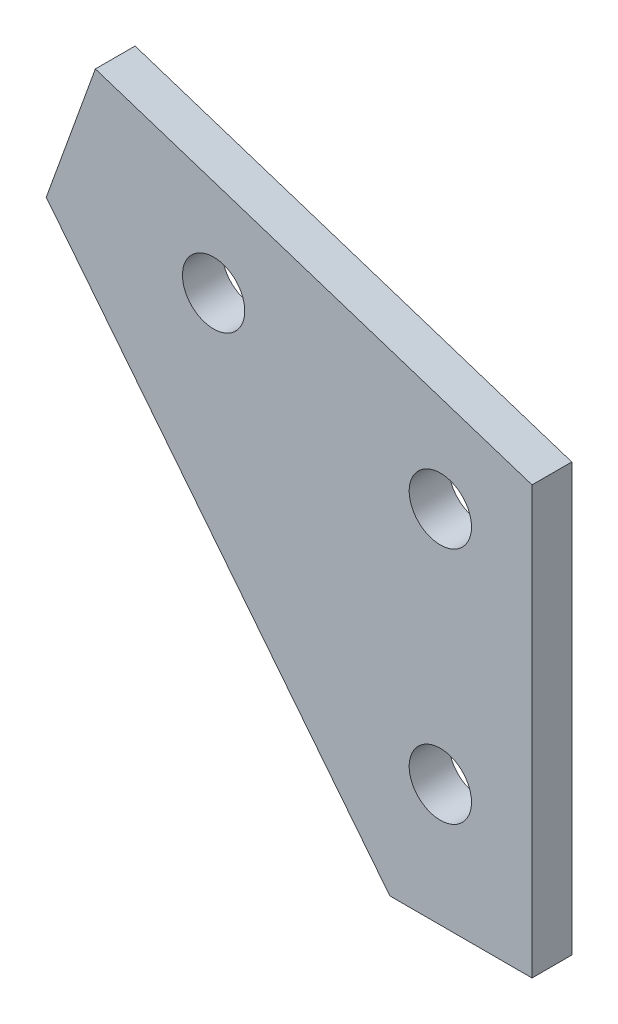
SolidWorks part; units mm, degrees
ref_plane "Front Plane" through (0, 0, 0) normal (0, 0, 1) x (1, 0, 0)
ref_plane "Top Plane" through (0, 0, 0) normal (0, 1, 0) x (1, 0, 0)
ref_plane "Right Plane" through (0, 0, 0) normal (1, 0, 0) x (0, 0, -1)
sketch "Sketch4" plane through (0, 0, 0) normal (0, 0, 1) x (1, 0, 0)
  line L0 (-40.992, 297.6034) -> (-42.1889, 293.9194) construction
  line L1 (-40.992, 297.6034) -> (-52.5693, 261.972) construction
  line L2 (-42.1889, 293.9194) -> (-7.2967, 282.5823)
  line L3 (-42.1889, 293.9194) -> (-46.1134, 283.0783)
  line L4 (-7.2967, 282.5823) -> (-7.2967, 248.4582)
  line L5 (-7.2967, 248.4582) -> (-18.6537, 248.4582)
  line L6 (-18.6537, 248.4582) -> (-46.1134, 283.0783)
  dimension "D1" = 3.8735
extrude "Boss-Extrude1" add sketch "Sketch4" along normal blind 3.175
hole_wizard "#10 Clearance Hole1" positions "Sketch5" profile "Sketch6" hole size "#10" standard "ANSI Inch" end condition through all
sketch "Sketch5" plane through (0, 0, 3.175) normal (0, 0, 1) x (1, 0, 0)
  point P0 (-32.7403, 283.1387)
  point P3 (-14.6226, 277.2519)
  point P6 (-14.6226, 258.2019)
sketch "Sketch6" plane through (-32.7403, 283.1387, 3.175) normal (1, 0, 0) x (0, -1, 0)
  line L0 (0, 0) -> (0, 3.175)
  line L1 (0, 3.175) -> (2.4892, 3.175)
  line L2 (2.4892, 3.175) -> (2.4892, 0)
  line L5 (2.4892, 0) -> (0, 0)
  line L11 (0, -6.35) -> (0, 107.95) construction
  dimension "Thru Hole Dia." = 4.9784
  dimension "Thru Hole Depth" = 3.175
